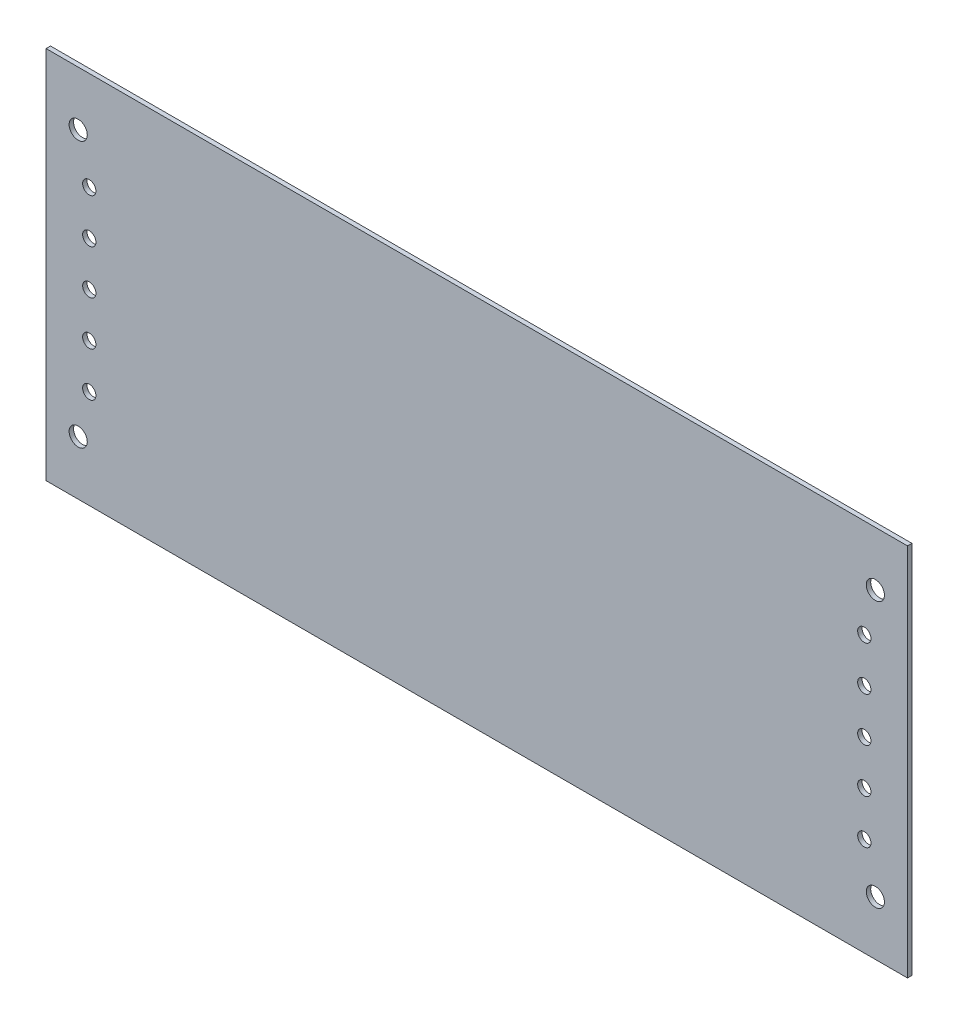
SolidWorks part; units mm, degrees
ref_plane "Front Plane" through (0, 0, 0) normal (0, 0, 1) x (1, 0, 0)
ref_plane "Top Plane" through (0, 0, 0) normal (0, 1, 0) x (1, 0, 0)
ref_plane "Right Plane" through (0, 0, 0) normal (1, 0, 0) x (0, 0, -1)
sketch "Model" plane through (0, 0, 0) normal (0, 0, 1) x (1, 0, 0)
  line L1 (194.5, -84.5) -> (-194.5, -84.5)
  line L2 (194.5, -84.5) -> (194.5, 84.5)
  line L3 (194.5, 84.5) -> (-194.5, 84.5)
  line L4 (-194.5, -84.5) -> (-194.5, 84.5)
  line L5 (194.5, -84.5) -> (-194.5, 84.5) construction
  line L6 (194.5, 84.5) -> (-194.5, -84.5) construction
  point P0 (0, 0)
  dimension "D1" = 389
  dimension "D2" = 169
extrude "Boss-Extrude1" add sketch "Model" along normal blind 2
sketch "Sketch1" plane through (0, 0, 2) normal (0, 0, 1) x (1, 0, 0)
  line L0 (0, 0) -> (0, 86) construction
  line L1 (0, 86) -> (175, 86) construction
  line L2 (0, 86) -> (-175, 86) construction
  line L3 (-175, 86) -> (-175, -86) construction
  line L4 (-175, -86) -> (175, -86) construction
  line L5 (175, -86) -> (175, 86) construction
  line L6 (-180, 60) -> (0, 60) construction
  line L7 (180, 60) -> (0, 60) construction
  line L8 (180, 60) -> (180, -60) construction
  line L9 (0, 0) -> (0, -60) construction
  line L10 (-180, 60) -> (-180, -60) construction
  circle A0 centre (-175, 0) radius 3
  circle A1 centre (175, 0) radius 3
  circle A2 centre (-175, 20) radius 3
  circle A3 centre (175, 20) radius 3
  circle A4 centre (-175, 40) radius 3
  circle A5 centre (175, 40) radius 3
  circle A6 centre (-180, 60) radius 4.1
  circle A7 centre (180, 60) radius 4.1
  circle A8 centre (-175, -20) radius 3
  circle A9 centre (175, -20) radius 3
  circle A10 centre (-175, -40) radius 3
  circle A11 centre (175, -40) radius 3
  circle A12 centre (-180, -60) radius 4.1
  circle A13 centre (180, -60) radius 4.1
  dimension "D3" = 6
  dimension "D4" = 6
  dimension "D5" = 8.2
  dimension "D6" = 8.2
  dimension "D7" = 8.2
  dimension "D8" = 8.2
  dimension "D9" = 6
  dimension "D10" = 6
  dimension "D11" = 6
  dimension "D12" = 6
  dimension "D13" = 6
  dimension "D14" = 6
  dimension "D15" = 6
  dimension "D16" = 6
  dimension "D1" = 175
  dimension "D2" = 175
  dimension "D17" = 180
  dimension "D18" = 180
extrude "Cut-Extrude1" cut sketch "Sketch1" against normal through all
